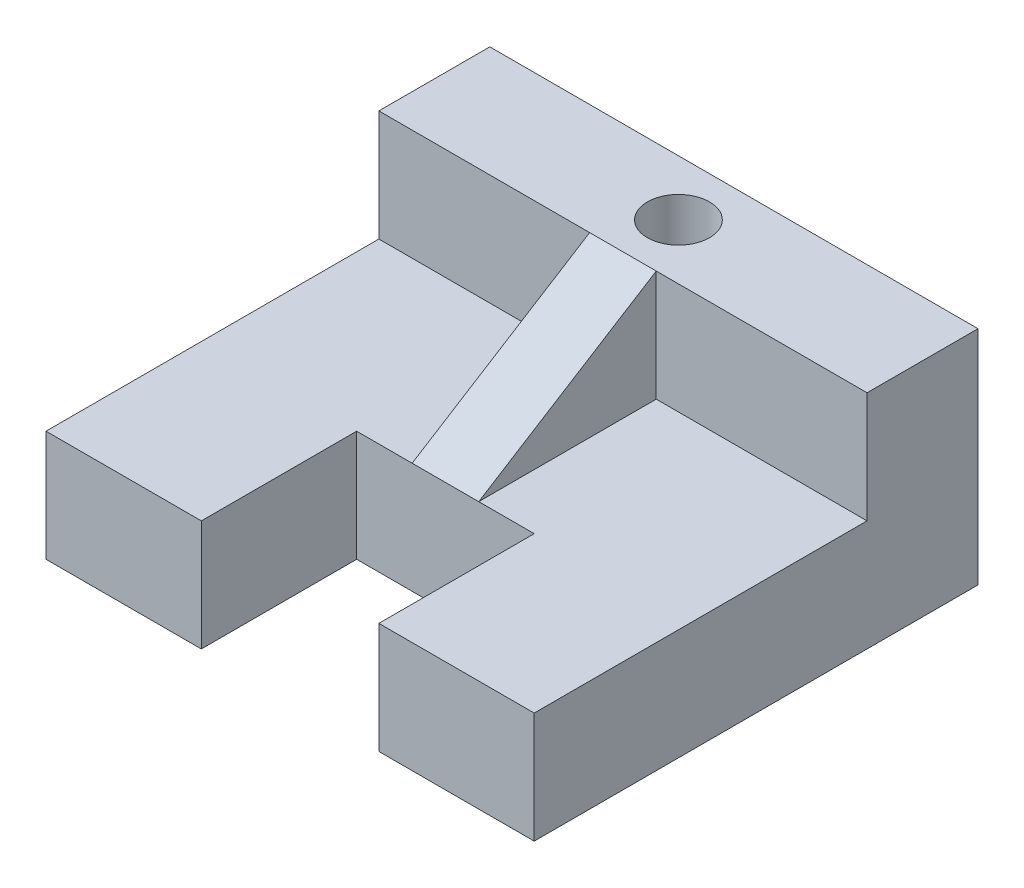
SolidWorks part; units mm, degrees
ref_plane "Спереди" through (0, 0, 0) normal (0, 0, 1) x (1, 0, 0)
ref_plane "Сверху" through (0, 0, 0) normal (0, 1, 0) x (1, 0, 0)
ref_plane "Справа" through (0, 0, 0) normal (1, 0, 0) x (0, 0, -1)
sketch "Эскиз1" plane through (0, 0, 0) normal (0, 1, 0) x (1, 0, 0)
  line L1 (-55, -50) -> (55, -50)
  line L2 (-55, -50) -> (-55, 50)
  line L3 (-55, 50) -> (55, 50)
  line L4 (55, -50) -> (55, 50)
  line L5 (-55, -50) -> (55, 50) construction
  line L6 (-55, 50) -> (55, -50) construction
  point P0 (0, 0)
  dimension "D1" = 110
  dimension "D2" = 100
extrude "Бобышка-Вытянуть1" add sketch "Эскиз1" along normal blind 25
sketch "Эскиз2" plane through (0, 25, 0) normal (0, 1, 0) x (1, 0, 0)
  line L0 (-55, 50) -> (-55, -50) construction
  line L1 (55, 50) -> (-55, 50)
  line L2 (55, 50) -> (55, 25)
  line L3 (55, 25) -> (-55, 25)
  line L4 (-55, 50) -> (-55, 25)
  dimension "D1" = 25
extrude "Бобышка-Вытянуть2" add sketch "Эскиз2" along normal blind 25
sketch "Эскиз3" plane through (0, 25, 0) normal (0, 1, 0) x (1, 0, 0)
  line L0 (-55, -50) -> (55, -50) construction
  line L1 (-20, -15) -> (20, -15)
  line L2 (-20, -15) -> (-20, -50)
  line L3 (-20, -50) -> (20, -50)
  line L4 (20, -15) -> (20, -50)
  line L5 (-20, -15) -> (20, -50) construction
  line L6 (-20, -50) -> (20, -15) construction
  point P0 (0, -32.5)
  dimension "D1" = 35
  dimension "D2" = 40
extrude "Вырез-Вытянуть1" cut sketch "Эскиз3" against normal through all
sketch "Эскиз4" plane through (0, 0, 0) normal (1, 0, 0) x (0, 0, -1)
  line L0 (25, 50) -> (-15, 25)
  line L1 (-50, 25) -> (25, 25) construction
rib "Ребро1" sketch "Эскиз4" sketch "Эскиз4" thickness 15 extrusion direction parallel to sketch draft on no parameters "D1"=15
sketch "Эскиз5" plane through (0, 50, 0) normal (0, 1, 0) x (1, 0, 0)
  line L0 (-55, 37.5) -> (55, 37.5) construction
  line L1 (-55, 50) -> (-55, 25) construction
  line L2 (55, 25) -> (55, 50) construction
  circle A0 centre (0, 37.5) radius 7
  dimension "D1" = 14
extrude "Вырез-Вытянуть2" cut sketch "Эскиз5" against normal through all
